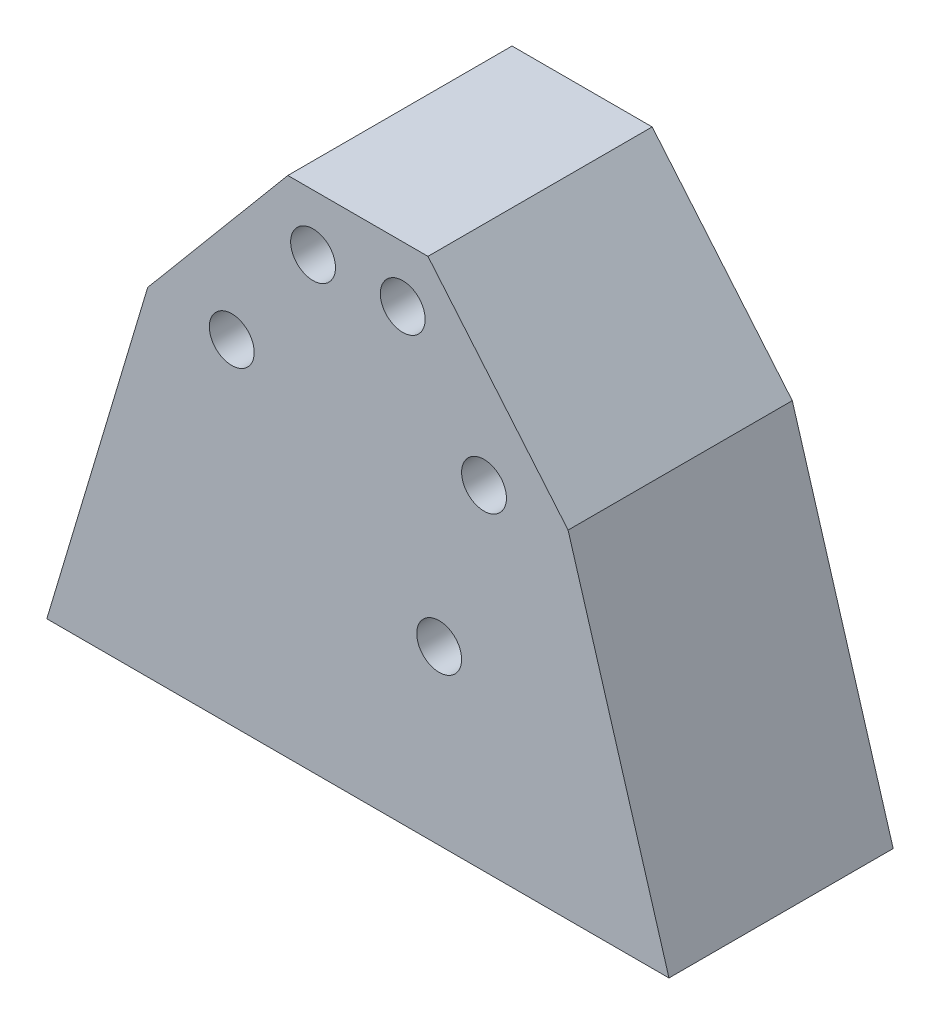
SolidWorks part; units mm, degrees
ref_plane "Piano frontale" through (0, 0, 0) normal (0, 0, 1) x (1, 0, 0)
ref_plane "Piano superiore" through (0, 0, 0) normal (0, 1, 0) x (1, 0, 0)
ref_plane "Piano destro" through (0, 0, 0) normal (1, 0, 0) x (0, 0, -1)
sketch "Sketch4" plane through (0, 0, 0) normal (0, 0, 1) x (1, 0, 0)
  line L1 (37.5, -45) -> (-37.5, -45)
  line L2 (12.5, 45) -> (-12.5, 45)
  line L3 (-37.5, -45) -> (-37.5, 15.2062)
  line L4 (0, 45) -> (0, -45) construction
  line L5 (37.5, 15.2062) -> (12.5, 45)
  line L6 (37.5, -45) -> (37.5, 15.2062)
  line L8 (-37.5, 15.2062) -> (-12.5, 45)
  circle A0 centre (14.5, -14.2791) radius 4
  circle A4 centre (22.5, 14.6346) radius 4
  circle A5 centre (22.5, 14.6346) radius 4
  circle A6 centre (8, 35) radius 4
  circle A7 centre (-8, 35) radius 4
  circle A8 centre (-22.5, 14.6346) radius 4
  circle A9 centre (-22.5, 14.6346) radius 4
  point P8 (17.0482, -14.8659)
  point P22 (-8, 33.9356)
  point P23 (0, 0)
  dimension "D2" = 8
  dimension "D3" = 8
  dimension "D4" = 8
  dimension "D1" = 25
  dimension "D5" = 90
  dimension "D6" = 50
  dimension "D7" = 16
  dimension "D8" = 30
  dimension "D9" = 75
  dimension "D10" = 25
  dimension "D11" = 10
  dimension "D12" = 45
  dimension "D13" = 23
extrude "Boss-Extrude1" add sketch "Sketch4" along normal blind 40 contours L2 L4 L1 L6 L5 A6 A0 A4 | L4 L2 L8 L3 L1 A8 A7
sketch "Sketch5" plane through (0, -45, 0) normal (0, -1, 0) x (1, 0, 0)
  line L0 (0, 40) -> (0, 0) construction
  line L1 (37.5, 40) -> (-37.5, 40) construction
  line L2 (-37.5, 20) -> (37.5, 20) construction
  line L3 (-37.5, 40) -> (-37.5, 0) construction
  line L4 (37.5, 40) -> (37.5, 0) construction
  circle A6 centre (-30, 7.15) radius 1.75
  circle A8 centre (30, 7.15) radius 1.75
  circle A9 centre (30, 32.85) radius 1.75
  circle A10 centre (-30, 32.85) radius 1.75
  point P23 (-65.3038, 49.3786)
  dimension "D1" = 12.85
  dimension "D2" = 30
extrude "Cut-Extrude1" cut sketch "Sketch5" against normal blind 15
sketch "Sketch6" plane through (0, 0, 0) normal (0, 0, -1) x (-1, 0, 0)
  line L120 (-34.3498, -2.4376) -> (-34.3498, -25.9971)
  line L125 (-34.3498, -25.9971) -> (25.0494, -25.9971)
  line L126 (25.0494, -2.4376) -> (25.0494, -25.9971)
  line L127 (-34.3498, -2.4376) -> (25.0494, -2.4376)
  point P0 (-54.0488, -10.102)
  point P68 (-53.1372, 7.4953)
  point P69 (-18.8963, -9.2898)
  point P70 (0, 0)
extrude "Cut-Extrude3" cut sketch "Sketch6" against normal blind 30
sketch "Sketch7" plane through (0, 0, 40) normal (0, 0, 1) x (1, 0, 0)
  line L0 (-37.5, 15.2062) -> (-55.5, -45)
  line L1 (-55.5, -45) -> (-37.5, -45)
  line L2 (-37.5, -45) -> (-37.5, 15.2062) construction
  line L3 (37.5, -45) -> (-37.5, -45) construction
  line L4 (-37.5, -45) -> (-37.5, 15.2062)
  line L5 (0, -35.7178) -> (0, 91.2491) construction
  line L6 (37.5, -45) -> (37.5, 15.2062)
  line L7 (55.5, -45) -> (37.5, -45)
  line L8 (37.5, 15.2062) -> (55.5, -45)
  dimension "D1" = 18
extrude "Boss-Extrude2" add sketch "Sketch7" against normal up to surface (40 mm away) up to face at (4.6502, -14.2173, 0)
